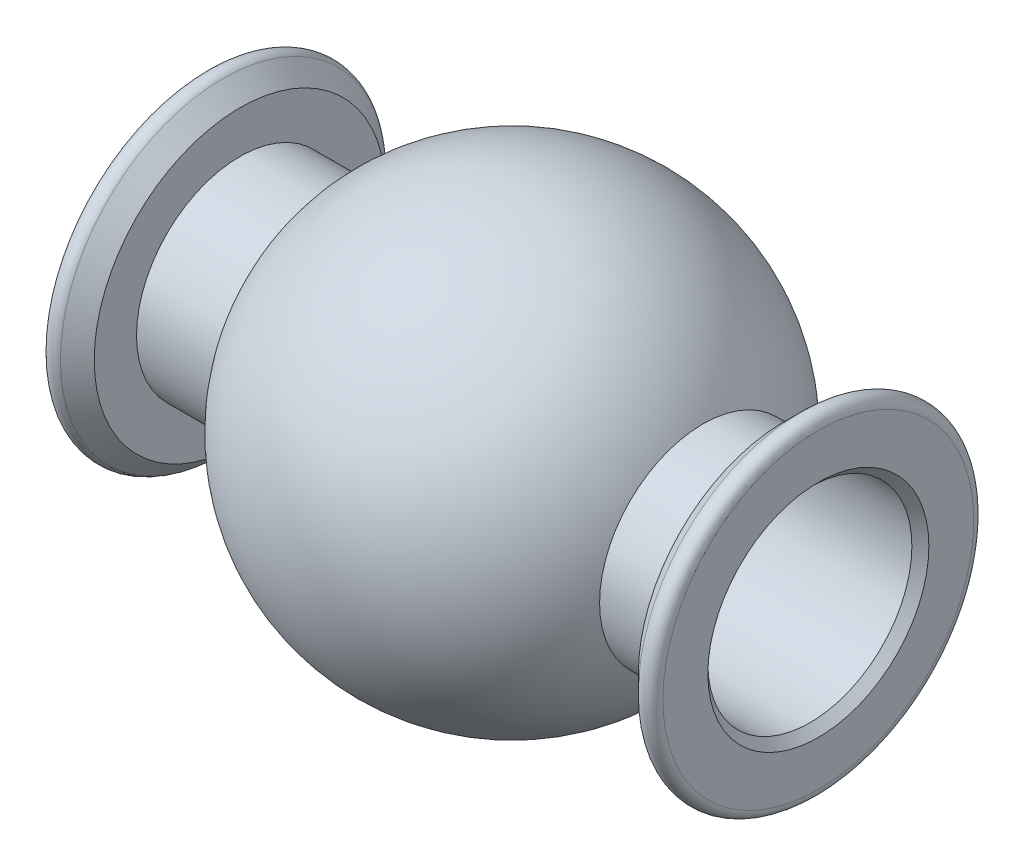
SolidWorks part; units mm, degrees
ref_plane "Front Plane" through (0, 0, 0) normal (0, 0, 1) x (1, 0, 0)
ref_plane "Top Plane" through (0, 0, 0) normal (0, 1, 0) x (1, 0, 0)
ref_plane "Right Plane" through (0, 0, 0) normal (1, 0, 0) x (0, 0, -1)
sketch "Sketch2" plane through (0, 0, 0) normal (0, 0, 1) x (1, 0, 0)
  line L0 (0, 12) -> (-8, 12) construction
  line L4 (-8, -1.5) -> (-8, 21.5695) construction
  line L7 (-13.6187, 15.0434) -> (-16, 15.0434)
  line L12 (-2.3813, 15.0434) -> (0, 15.0434)
  line L13 (-16, 15.0434) -> (-16, 16.2857)
  line L15 (-16, 16.2857) -> (-16.4972, 16.7829)
  line L16 (-17.0093, 16.5707) -> (-17.0093, 15.25)
  line L17 (-17.0093, 15.25) -> (-16.5047, 14.7453)
  line L18 (-16.5047, 14.7453) -> (-16.5047, 12)
  line L27 (0.5047, 14.7453) -> (0.5047, 12)
  line L28 (1.0093, 15.25) -> (0.5047, 14.7453)
  line L29 (1.0093, 16.5707) -> (1.0093, 15.25)
  line L30 (0, 16.2857) -> (0.4972, 16.7829)
  line L31 (0, 15.0434) -> (0, 16.2857)
  line L32 (-16.5047, 12) -> (0.5047, 12)
  arc A0 (-17.0093, 16.5707) -> (-16.4972, 16.7829) centre (-16.7093, 16.5707) cw
  arc A1 (-2.3813, 15.0434) -> (-13.6187, 15.0434) centre (-8, 12) ccw
  arc A2 (1.0093, 16.5707) -> (0.4972, 16.7829) centre (0.7093, 16.5707) ccw
  point P6 (-17.0093, 17.295)
  point P12 (1.0093, 17.295)
  point P35 (-16.5047, 12)
  point P46 (0.5047, 12)
  dimension "D1" = 0.3
  dimension "D2" = 0.3
  dimension "D3" = 6.39
revolve "Revolve2" add sketch "Sketch2" angle 360 about L32
sketch "Sketch3" plane through (1.0093, 0, 0) normal (1, 0, 0) x (0, 0, -1)
  circle A0 centre (0, 12) radius 3
  dimension "D1" = 6
extrude "Cut-Extrude4" cut sketch "Sketch3" against normal blind 24
